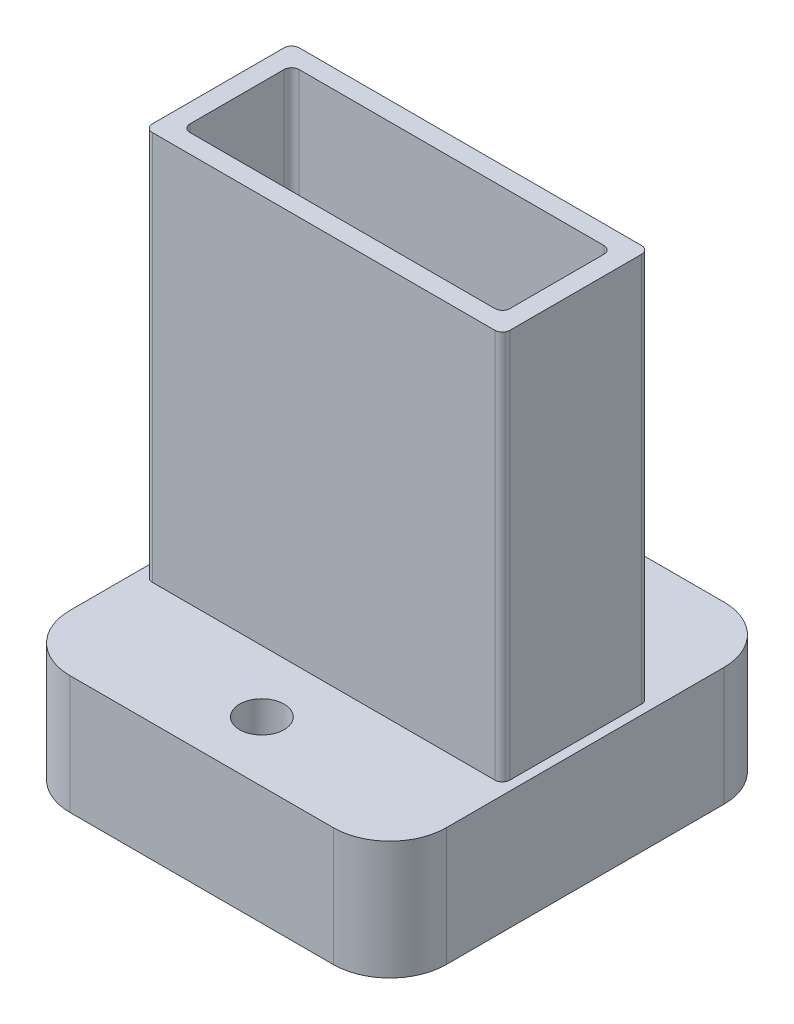
SolidWorks part; units mm, degrees
ref_plane "Front Plane" through (0, 0, 0) normal (0, 0, 1) x (1, 0, 0)
ref_plane "Top Plane" through (0, 0, 0) normal (0, 1, 0) x (1, 0, 0)
ref_plane "Right Plane" through (0, 0, 0) normal (1, 0, 0) x (0, 0, -1)
sketch "Sketch1" plane through (0, 0, 0) normal (0, 1, 0) x (1, 0, 0)
  line L0 (11.557, 4.953) -> (-11.557, 4.953)
  line L7 (-12.065, -4.445) -> (-12.065, 4.445)
  line L8 (11.557, -4.953) -> (-11.557, -4.953)
  line L9 (12.065, -4.445) -> (12.065, 4.445)
  arc A0 (11.557, -4.953) -> (12.065, -4.445) centre (11.557, -4.445) ccw
  arc A1 (11.557, 4.953) -> (12.065, 4.445) centre (11.557, 4.445) cw
  arc A2 (-12.065, -4.445) -> (-11.557, -4.953) centre (-11.557, -4.445) ccw
  arc A3 (-11.557, 4.953) -> (-12.065, 4.445) centre (-11.557, 4.445) ccw
  point P0 (0, 0)
  point P10 (0, 0)
  point P19 (0, 0)
extrude "Boss-Extrude1" add sketch "Sketch1" along normal blind 23.622
sketch "Sketch2" plane through (0, 23.622, 0) normal (0, 1, 0) x (1, 0, 0)
  line L0 (11.557, 4.953) -> (-11.557, 4.953)
  line L1 (10.287, -3.683) -> (-10.287, -3.683)
  line L2 (10.795, -3.175) -> (10.795, 3.175)
  line L3 (10.287, 3.683) -> (-10.287, 3.683)
  line L4 (-10.795, -3.175) -> (-10.795, 3.175)
  line L5 (10.795, -3.683) -> (-10.795, 3.683) construction
  line L6 (10.795, 3.683) -> (-10.795, -3.683) construction
  line L7 (-12.065, -4.445) -> (-12.065, 4.445)
  line L8 (11.557, -4.953) -> (-11.557, -4.953)
  line L9 (12.065, -4.445) -> (12.065, 4.445)
  line L10 (12.065, -4.953) -> (-12.065, -4.953) construction
  line L11 (12.065, -4.953) -> (12.065, 4.953) construction
  line L12 (12.065, 4.953) -> (-12.065, 4.953) construction
  line L13 (10.795, -3.683) -> (-10.795, -3.683) construction
  line L14 (10.795, -3.683) -> (10.795, 3.683) construction
  line L15 (10.795, 3.683) -> (-10.795, 3.683) construction
  line L16 (-10.795, -3.683) -> (-10.795, 3.683) construction
  line L17 (-12.065, -4.953) -> (-12.065, 4.953) construction
  arc A0 (11.557, -4.953) -> (12.065, -4.445) centre (11.557, -4.445) ccw
  arc A1 (11.557, 4.953) -> (12.065, 4.445) centre (11.557, 4.445) cw
  arc A2 (10.287, -3.683) -> (10.795, -3.175) centre (10.287, -3.175) ccw
  arc A3 (10.795, 3.175) -> (10.287, 3.683) centre (10.287, 3.175) ccw
  arc A4 (-10.287, 3.683) -> (-10.795, 3.175) centre (-10.287, 3.175) ccw
  arc A5 (-10.287, -3.683) -> (-10.795, -3.175) centre (-10.287, -3.175) cw
  arc A6 (-12.065, -4.445) -> (-11.557, -4.953) centre (-11.557, -4.445) ccw
  arc A7 (-11.557, 4.953) -> (-12.065, 4.445) centre (-11.557, 4.445) ccw
  point P0 (0, 0)
  point P10 (0, 0)
  dimension "D4" = 0.508
  dimension "D1" = 21.59
  dimension "D2" = 7.366
  dimension "D3" = 1.27
extrude "Boss-Extrude2" add sketch "Sketch2" along normal blind 10.668
sketch "Sketch4" plane through (0, 0, 0) normal (0, 1, 0) x (1, 0, 0)
  line L3 (-8.89, -13.184) -> (8.89, -13.184)
  line L5 (-8.271, 0) -> (6.4954, 0) construction
  line L6 (-8.89, 13.184) -> (8.89, 13.184)
  line L10 (-12.7, 9.374) -> (-12.7, -9.374)
  line L11 (12.7, 9.374) -> (12.7, -9.374)
  circle A0 centre (0, -9.12) radius 1.5
  arc A1 (8.89, -13.184) -> (12.7, -9.374) centre (8.89, -9.374) ccw
  arc A2 (-12.7, -9.374) -> (-8.89, -13.184) centre (-8.89, -9.374) ccw
  circle A3 centre (0, 9.12) radius 1.5
  arc A4 (8.89, 13.184) -> (12.7, 9.374) centre (8.89, 9.374) cw
  arc A5 (-12.7, 9.374) -> (-8.89, 13.184) centre (-8.89, 9.374) cw
  dimension "D1" = 3
  dimension "D4" = 3.81
  dimension "D3" = 4.064
extrude "Boss-Extrude3" add sketch "Sketch4" along normal blind 8
